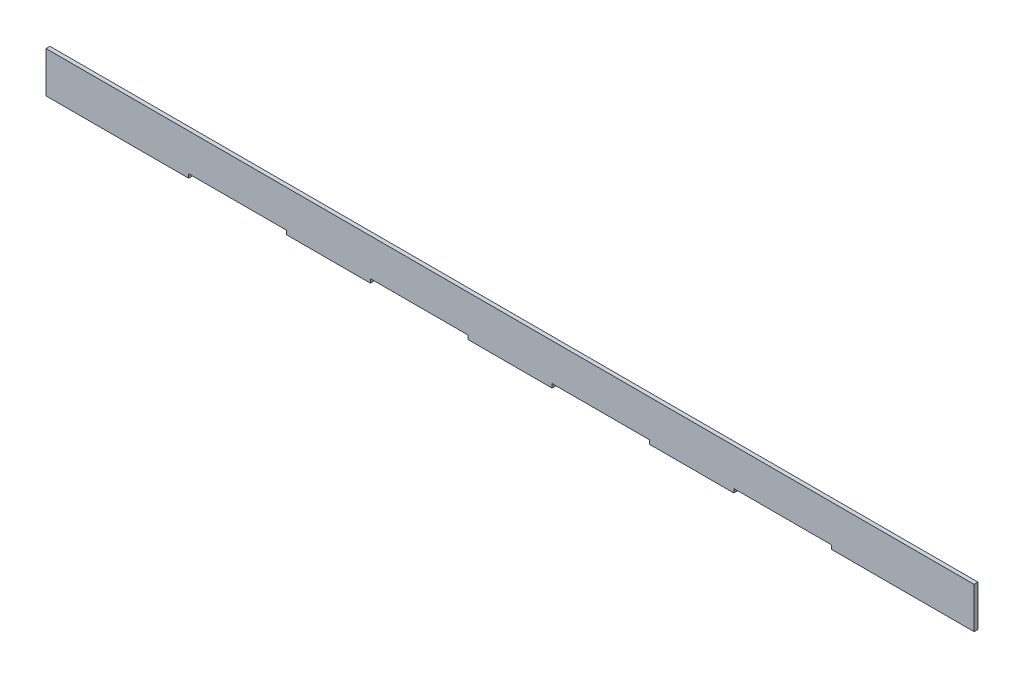
SolidWorks part; units mm, degrees
ref_plane "Front Plane" through (0, 0, 0) normal (0, 0, 1) x (1, 0, 0)
ref_plane "Top Plane" through (0, 0, 0) normal (0, 1, 0) x (1, 0, 0)
ref_plane "Right Plane" through (0, 0, 0) normal (1, 0, 0) x (0, 0, -1)
sketch "Sketch1" plane through (0, 0, 0) normal (0, 0, 1) x (1, 0, 0)
  line L1 (-237.5, -10.5) -> (237.5, -10.5)
  line L2 (-237.5, -10.5) -> (-237.5, 10.5)
  line L3 (-237.5, 10.5) -> (237.5, 10.5)
  line L4 (237.5, -10.5) -> (237.5, 10.5)
  line L5 (0, 10.5) -> (0, -10.5) construction
  line L6 (-237.5, 0) -> (237.5, 0) construction
  point P0 (0, 0)
  dimension "D1" = 21
  dimension "D2" = 475
extrude "Boss-Extrude1" add sketch "Sketch1" along normal blind 2
sketch "Sketch2" plane through (0, 0, 2) normal (0, 0, 1) x (1, 0, 0)
  line L0 (-237.5, -10.5) -> (-232.5, -10.5)
  line L1 (-237.5, -10.5) -> (237.5, -10.5) construction
  line L2 (-232.5, -10.5) -> (-164.5, -10.5)
  line L3 (-164.5, -10.5) -> (-114.5, -10.5)
  line L4 (-114.5, -10.5) -> (-71.5, -10.5)
  line L5 (-71.5, -10.5) -> (-21.5, -10.5)
  line L6 (-21.5, -10.5) -> (21.5, -10.5)
  line L7 (21.5, -10.5) -> (71.5, -10.5)
  line L8 (71.5, -10.5) -> (164.5, -10.5)
  line L9 (164.5, -10.5) -> (114.5, -10.5)
  line L10 (164.5, -10.5) -> (232.5, -10.5)
  line L12 (-164.5, -10.5) -> (-114.5, -10.5)
  line L13 (-164.5, -10.5) -> (-164.5, -8.5)
  line L14 (-164.5, -8.5) -> (-114.5, -8.5)
  line L15 (-114.5, -10.5) -> (-114.5, -8.5)
  line L16 (-71.5, -10.5) -> (-21.5, -10.5)
  line L17 (-71.5, -10.5) -> (-71.5, -8.5)
  line L18 (-71.5, -8.5) -> (-21.5, -8.5)
  line L19 (-21.5, -10.5) -> (-21.5, -8.5)
  line L20 (21.5, -10.5) -> (71.5, -10.5)
  line L21 (21.5, -10.5) -> (21.5, -8.5)
  line L22 (21.5, -8.5) -> (71.5, -8.5)
  line L23 (71.5, -10.5) -> (71.5, -8.5)
  line L24 (114.5, -10.5) -> (164.5, -10.5)
  line L25 (114.5, -10.5) -> (114.5, -8.5)
  line L26 (114.5, -8.5) -> (164.5, -8.5)
  line L27 (164.5, -10.5) -> (164.5, -8.5)
  line M4 (-237.5, -10.5) -> (237.5, -10.5)
  dimension "D1" = 5
  dimension "D2" = 68
  dimension "D3" = 50
  dimension "D4" = 43
  dimension "D5" = 50
  dimension "D6" = 43
  dimension "D7" = 50
  dimension "D8" = 43
  dimension "D9" = 50
  dimension "D10" = 68
  dimension "D11" = 5
  dimension "D12" = 2
  dimension "D13" = 2
  dimension "D14" = 2
  dimension "D15" = 2
extrude "Cut-Extrude1" cut sketch "Sketch2" against normal blind 2 contours L19 L18 L17 M4 | L15 L14 L13 M4 | L23 L22 L21 M4 | L8 L27 L26 L25
